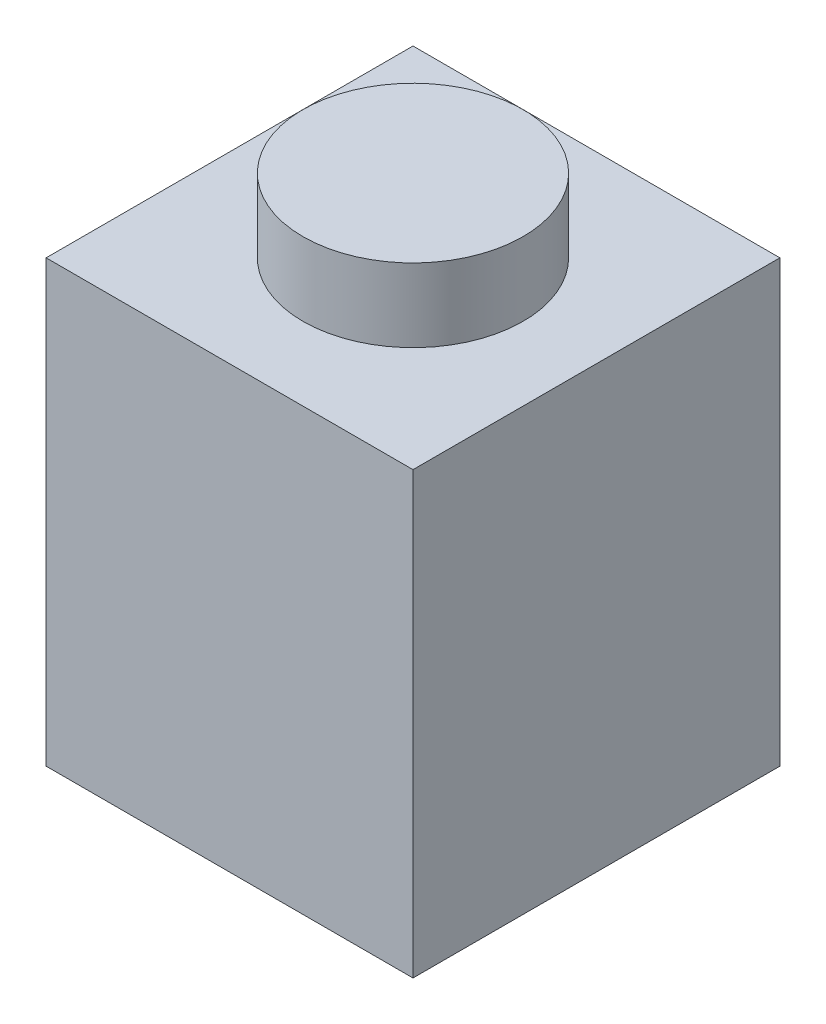
SolidWorks part; units mm, degrees
ref_plane "Front Plane" through (0, 0, 0) normal (0, 0, 1) x (1, 0, 0)
ref_plane "Top Plane" through (0, 0, 0) normal (0, 1, 0) x (1, 0, 0)
ref_plane "Right Plane" through (0, 0, 0) normal (1, 0, 0) x (0, 0, -1)
sketch "Sketch1" plane through (0, 0, 0) normal (0, 1, 0) x (1, 0, 0)
  line L1 (0, 0) -> (8, 0)
  line L2 (0, 0) -> (0, 8)
  line L3 (0, 8) -> (8, 8)
  line L4 (8, 0) -> (8, 8)
  dimension "D1" = 8
  dimension "D2" = 8
extrude "Boss-Extrude1" add sketch "Sketch1" along normal blind 9.6
sketch "Sketch2" plane through (0, 9.6, 0) normal (0, 1, 0) x (1, 0, 0)
  line L0 (4, 0) -> (4, 8) construction
  line L1 (0, 0) -> (8, 0) construction
  line L2 (8, 8) -> (0, 8) construction
  line L3 (8, 0) -> (8, 4) construction
  line L4 (8, 0) -> (8, 8) construction
  line L5 (8, 4) -> (4, 4) construction
  circle A0 centre (4, 4) radius 2.4
  dimension "D3" = 4.8
  dimension "D1" = 4
  dimension "D2" = 4
extrude "Boss-Extrude2" add sketch "Sketch2" along normal blind 1.6
shell "Shell1" thickness 1.6
